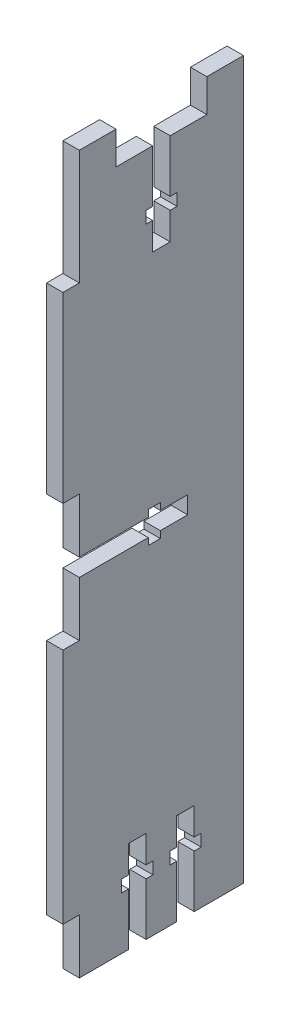
SolidWorks part; units mm, degrees
ref_plane "Front Plane" through (0, 0, 0) normal (0, 0, 1) x (1, 0, 0)
ref_plane "Top Plane" through (0, 0, 0) normal (0, 1, 0) x (1, 0, 0)
ref_plane "Right Plane" through (0, 0, 0) normal (1, 0, 0) x (0, 0, -1)
sketch "Sketch1" plane through (0, 0, 0) normal (1, 0, 0) x (0, 0, -1)
  line L0 (-2.8, -60) -> (2.8, -60)
  line L1 (6, -60) -> (6, -50.4)
  line L2 (-15, 60) -> (-15, 55)
  line L3 (-15, 60) -> (-15, 71)
  line L4 (15, -60) -> (15, 60)
  line L5 (-15, -60) -> (15, 60) construction
  line L6 (-15, 60) -> (15, -60) construction
  line L7 (6, -50.4) -> (7.25, -50.4)
  line L8 (7.25, -50.4) -> (7.25, -48.2)
  line L9 (7.25, -48.2) -> (6, -48.2)
  line L10 (6, -48.2) -> (6, -43.2)
  line L11 (6, -43.2) -> (2.8, -43.2)
  line L12 (2.8, -43.2) -> (2.8, -48.2)
  line L13 (2.8, -48.2) -> (1.55, -48.2)
  line L14 (1.55, -48.2) -> (1.55, -50.4)
  line L15 (1.55, -50.4) -> (2.8, -50.4)
  line L16 (2.8, -50.4) -> (2.8, -60)
  line L17 (-2.8, -60) -> (-2.8, -50.4)
  line L18 (-2.8, -50.4) -> (-1.55, -50.4)
  line L19 (-1.55, -50.4) -> (-1.55, -48.2)
  line L20 (-1.55, -48.2) -> (-2.8, -48.2)
  line L21 (-2.8, -48.2) -> (-2.8, -43.2)
  line L22 (-7.25, -48.2) -> (-6, -48.2)
  line L23 (-6, -48.2) -> (-6, -43.2)
  line L24 (-6, -43.2) -> (-2.8, -43.2)
  line L25 (-7.25, -48.2) -> (-7.25, -50.4)
  line L26 (-7.25, -50.4) -> (-6, -50.4)
  line L27 (-6, -50.4) -> (-6, -60)
  line L28 (-15, -60) -> (-6, -60)
  line L29 (-2.8, -43.2) -> (-2.8095, -43.0254)
  line L30 (15, 60) -> (15, 71)
  line L31 (1.6, 65) -> (1.6, 55.4)
  line L32 (1.6, 55.4) -> (2.85, 55.4)
  line L33 (-1.6, 53.2) -> (-1.6, 48.2)
  line L34 (2.85, 55.4) -> (2.85, 53.2)
  line L35 (2.85, 53.2) -> (1.6, 53.2)
  line L36 (1.6, 53.2) -> (1.6, 48.2)
  line L37 (-1.6, 48.2) -> (1.6, 48.2)
  line L38 (-1.6, 53.2) -> (-2.85, 53.2)
  line L39 (-2.85, 53.2) -> (-2.85, 55.4)
  line L40 (-2.85, 55.4) -> (-1.6, 55.4)
  line L41 (-1.6, 55.4) -> (-1.6, 65)
  line L42 (-15, 6.6) -> (-2.4, 6.6)
  line L43 (-2.4, 6.6) -> (-2.4, 7.85)
  line L44 (-2.4, 7.85) -> (-0.2, 7.85)
  line L45 (-0.2, 7.85) -> (-0.2, 6.6)
  line L46 (-0.2, 6.6) -> (4.8, 6.6)
  line L47 (4.8, 6.6) -> (4.8, 3.4)
  line L48 (4.8, 3.4) -> (-0.2, 3.4)
  line L49 (-0.2, 3.4) -> (-0.2, 2.15)
  line L50 (-0.2, 2.15) -> (-2.4, 2.15)
  line L51 (-2.4, 2.15) -> (-2.4, 3.4)
  line L52 (-2.4, 3.4) -> (-15, 3.4)
  line L53 (-15, 3.4) -> (-15, -6.6)
  line L54 (-18, 50) -> (-15, 50)
  line L55 (-18, 50) -> (-18, 16.6)
  line L56 (-18, 16.6) -> (-15, 16.6)
  line L57 (-15, 16.6) -> (-15, 6.6)
  line L58 (-15, -6.6) -> (-18, -6.6)
  line L59 (-18, -6.6) -> (-18, -50)
  line L60 (-18, -50) -> (-15, -50)
  line L61 (-15, -50) -> (-15, -60)
  line L62 (15, 71) -> (8.3, 71)
  line L63 (-8.3, 71) -> (-8.3, 65)
  line L64 (-1.6, 65) -> (-8.3, 65)
  line L65 (8.3, 65) -> (1.6, 65)
  line L66 (-15, 71) -> (-8.3, 71)
  line L67 (8.3, 71) -> (8.3, 65)
  line L68 (-15, 50) -> (-15, 55)
  line L70 (6, -60) -> (15, -60)
  point P0 (0, 0)
extrude "Boss-Extrude1" add sketch "Sketch1" along normal blind 3 contours L1 L70 L4 L30 L62 L67 L65 L31 L32 L34 L35 L36 L37 L33 L38 L39 L40 L41 L64 L63 L66 L3 L2 L68 L54 L55 L56 L57 L42 L43 L44 L45 L46 L47 L48 L49 L50 L51 L52 L53 L58 L59 L60 L61 L28 L27 L26 L25 L22 L23 L24
